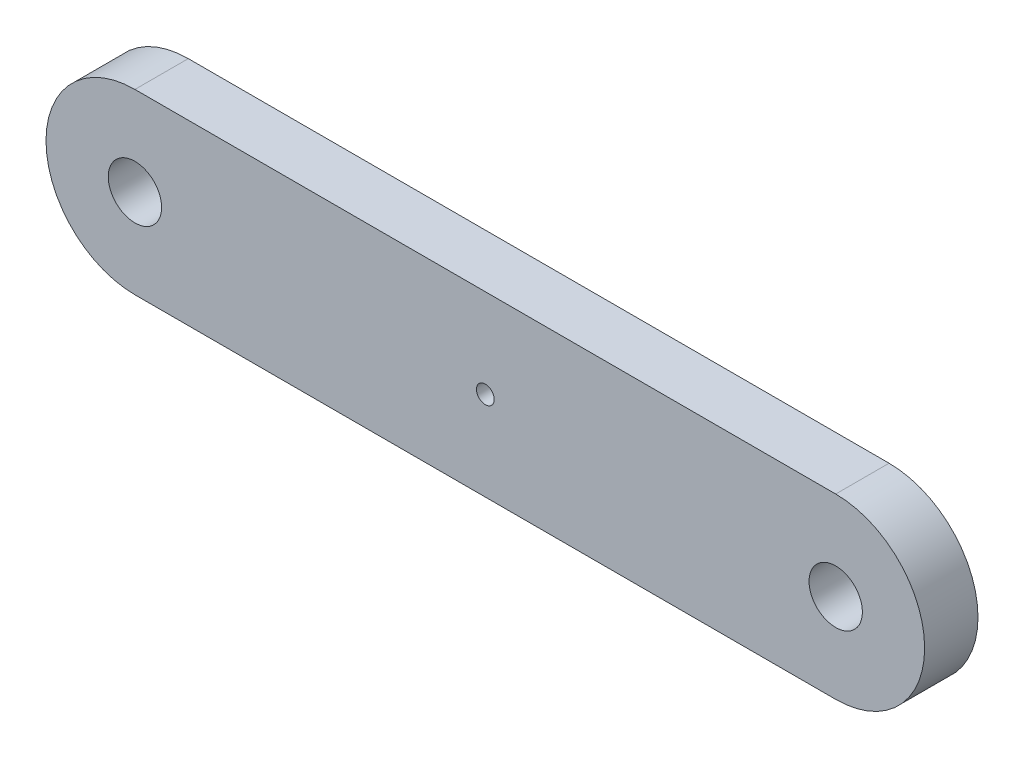
SolidWorks part; units mm, degrees
material "Acrylic (Medium-high impact)"
ref_plane "Front Plane" through (0, 0, 0) normal (0, 0, 1) x (1, 0, 0)
ref_plane "Top Plane" through (0, 0, 0) normal (0, 1, 0) x (1, 0, 0)
ref_plane "Right Plane" through (0, 0, 0) normal (1, 0, 0) x (0, 0, -1)
sketch "Sketch1" plane through (0, 0, 0) normal (0, 0, 1) x (1, 0, 0)
  line L0 (0, 0) -> (39.4, 0) construction
  line L1 (0, 5) -> (39.4, 5)
  line L2 (0, -5) -> (39.4, -5)
  arc A0 (0, 5) -> (0, -5) centre (0, 0) ccw
  arc A1 (39.4, -5) -> (39.4, 5) centre (39.4, 0) ccw
  circle A2 centre (0, 0) radius 1.5
  circle A3 centre (39.4, 0) radius 1.5
  circle A4 centre (19.7, 0) radius 0.5
  point P3 (19.7, 0)
  dimension "D1" = 3
  dimension "D2" = 3
  dimension "D5" = 1
  dimension "D3" = 39.4
  dimension "D4" = 10
extrude "Boss-Extrude1" add sketch "Sketch1" along normal blind 3
